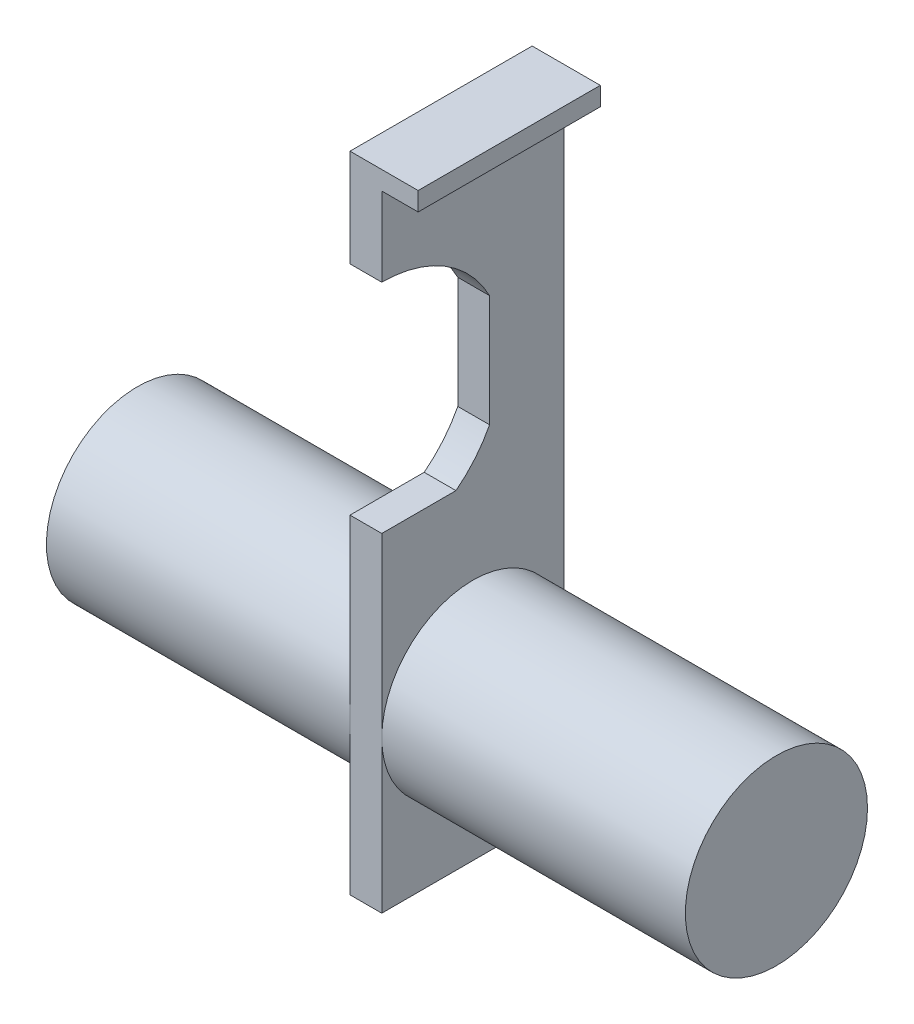
SolidWorks part; units mm, degrees
ref_plane "Front Plane" through (0, 0, 0) normal (0, 0, 1) x (1, 0, 0)
ref_plane "Top Plane" through (0, 0, 0) normal (0, 1, 0) x (1, 0, 0)
ref_plane "Right Plane" through (0, 0, 0) normal (1, 0, 0) x (0, 0, -1)
sketch "Sketch2" plane through (0, 0, 0) normal (0, 0, 1) x (1, 0, 0)
  line L0 (1.329, -2.5915) -> (1.329, 0.7141)
  line L2 (1.329, 1.4926) -> (2.8507, 1.4926)
  line L3 (2.8507, 1.4926) -> (2.8507, 0.7141)
  line L4 (2.8507, 0.7141) -> (1.329, 0.7141)
  line L5 (0, 0.7141) -> (0, -2.5915)
  line L6 (1.329, 1.4926) -> (0, 1.4926)
  line L7 (0, 1.4926) -> (0, 0.7141)
  line L9 (0, -2.5915) -> (0, -12.7515)
  line L10 (0, -12.7515) -> (1.329, -12.7515)
  line L11 (1.329, -12.7515) -> (1.329, -2.5915)
extrude "Boss-Extrude1" add sketch "Sketch2" along normal blind 7.62
sketch "Sketch4" plane through (1.329, 0, 0) normal (1, 0, 0) x (0, 0, -1)
  line L0 (-7.62, -12.7515) -> (-7.62, -2.5915) construction
  line L1 (-7.62, -12.7515) -> (-7.62, 0.7141) construction
  line L3 (-3.1107, -5.3321) -> (-3.1107, -10.0109)
  line L5 (-7.62, -11.693) -> (-4.5162, -11.693)
  line L6 (-7.62, -11.693) -> (-7.62, -2.5915)
  arc A0 (-4.5162, -11.693) -> (-3.1107, -10.0109) centre (-7.62, -7.6715) ccw
  arc A1 (-3.1107, -5.3321) -> (-7.62, -2.5915) centre (-7.62, -7.6715) ccw
extrude "Cut-Extrude2" cut sketch "Sketch4" against normal blind 6.35
sketch "Sketch7" plane through (0, -12.7515, 0) normal (0, -1, 0) x (1, 0, 0)
  line L4 (0, 0) -> (1.329, 0)
  line L5 (1.329, 0) -> (1.329, 7.62)
  line L6 (1.329, 7.62) -> (0, 7.62)
  line L7 (0, 7.62) -> (0, 0)
  line L8 (0, 0) -> (1.329, 0)
  line L9 (1.329, 0) -> (1.329, 7.62)
  line L10 (1.329, 7.62) -> (0, 7.62)
  line L11 (0, 7.62) -> (0, 0)
  dimension "D1" = 0
extrude "Boss-Extrude2" add sketch "Sketch7" along normal blind 12.7
sketch "Sketch8" plane through (1.329, 0, 0) normal (1, 0, 0) x (0, 0, -1)
  line L0 (0, -25.4515) -> (0, -19.1015) construction
  line L1 (0, -25.4515) -> (0, 0.7141) construction
  line L2 (0, -19.1015) -> (-3.81, -19.1015) construction
  circle A0 centre (-3.81, -19.1015) radius 3.81
extrude "Boss-Extrude3" add sketch "Sketch8" along normal blind 12.7
sketch "Sketch9" plane through (0, 0, 0) normal (-1, 0, 0) x (0, 0, 1)
  line L0 (0, -19.1015) -> (3.81, -19.1015) construction
  circle A0 centre (3.81, -19.1015) radius 3.81
extrude "Boss-Extrude4" add sketch "Sketch9" along normal blind 12.7
